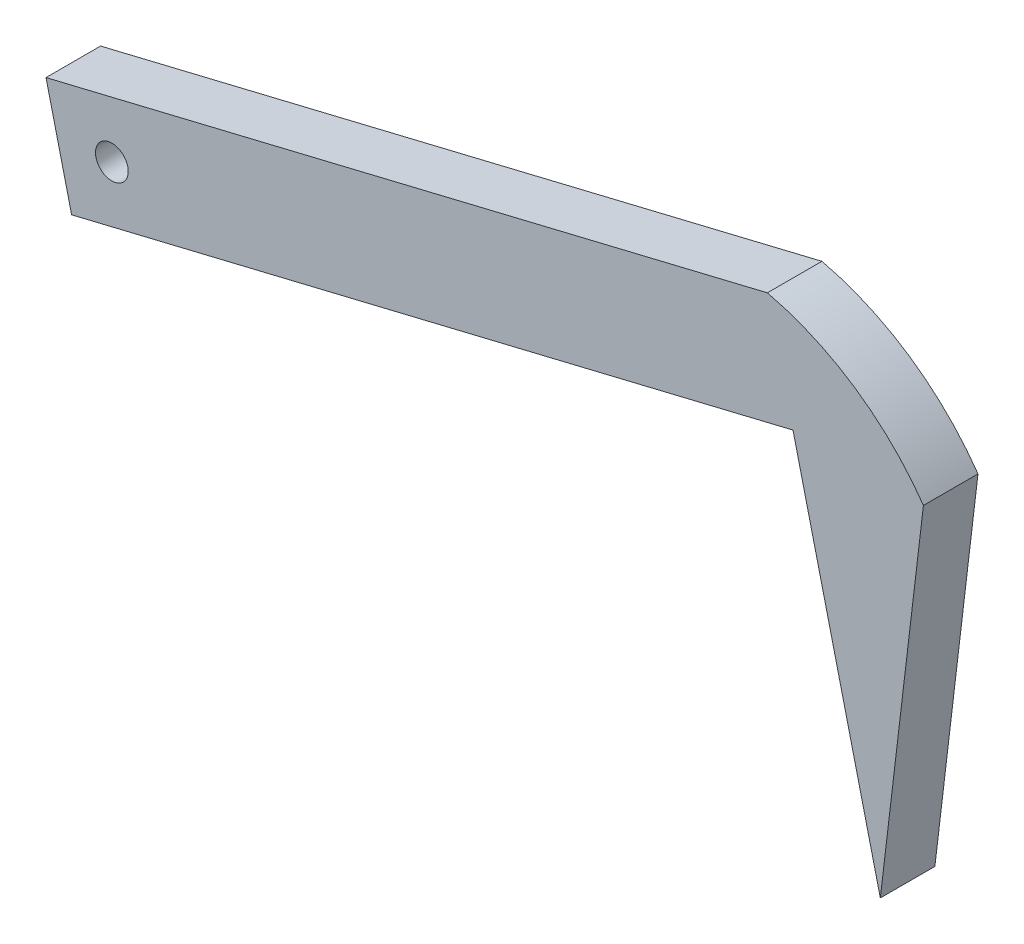
SolidWorks part; units mm, degrees
ref_plane "Plan de face" through (0, 0, 0) normal (0, 0, 1) x (1, 0, 0)
ref_plane "Plan de dessus" through (0, 0, 0) normal (0, 1, 0) x (1, 0, 0)
ref_plane "Plan de droite" through (0, 0, 0) normal (1, 0, 0) x (0, 0, -1)
sketch "Esquisse1" plane through (0, 0, 0) normal (0, 0, 1) x (1, 0, 0)
  line L1 (80.3993, 6.2467) -> (76.449, -26.8794)
  line L3 (68.4469, 6.2467) -> (2.3481, -9.7204)
  line L4 (2.3481, -9.7204) -> (0, 0)
  line L5 (0, 0) -> (66.0988, 15.9671)
  line L6 (68.4469, 6.2467) -> (76.449, -26.8794)
  arc A0 (66.0988, 15.9671) -> (80.3993, 6.2467) centre (60.4878, -7.6673) cw
  circle A1 centre (6.0343, -3.6862) radius 1.5
  point P6 (60.0755, 6.7657)
  point P9 (67.1934, 7.8135)
  point P10 (59.8723, 8.2635)
  point P11 (60.1371, 6.2467)
  point P18 (1.1741, -4.8602)
  dimension "D5" = 3
  dimension "D1" = 10
  dimension "D2" = 80
  dimension "D3" = 68
  dimension "D4" = 68
  dimension "D6" = 5
  dimension "D7" = 5
extrude "Boss.-Extru.1" add sketch "Esquisse1" along normal blind 5
